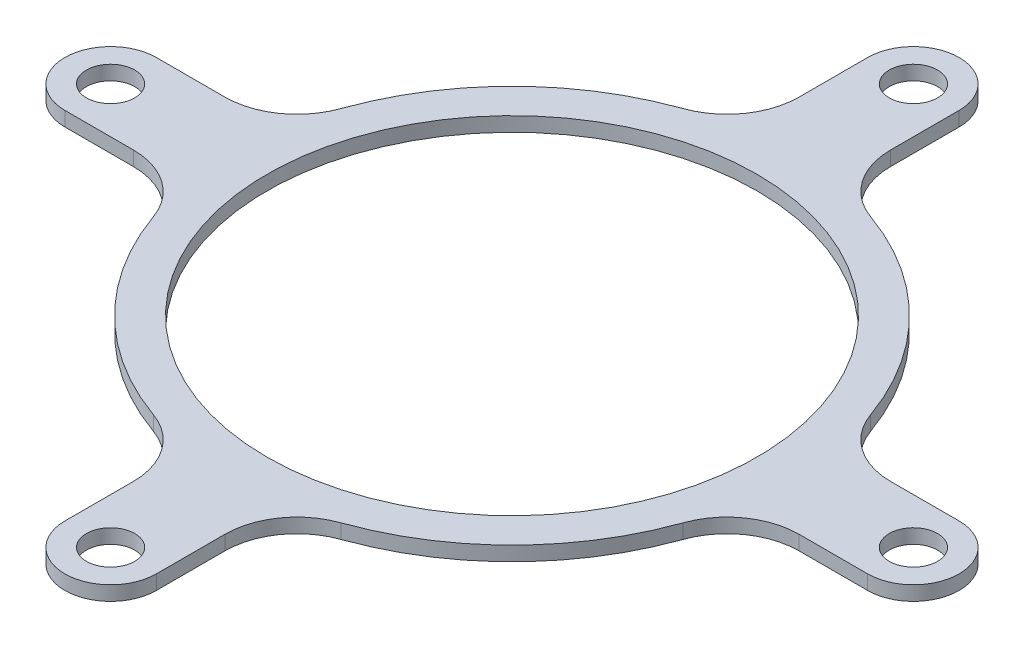
SolidWorks part; units mm, degrees
ref_plane "Front Plane" through (0, 0, 0) normal (0, 0, 1) x (1, 0, 0)
ref_plane "Top Plane" through (0, 0, 0) normal (0, 1, 0) x (1, 0, 0)
ref_plane "Right Plane" through (0, 0, 0) normal (1, 0, 0) x (0, 0, -1)
sketch "Sketch1" plane through (0, 0, 0) normal (0, 1, 0) x (1, 0, 0)
  circle A0 centre (0, 0) radius 34
  circle A1 centre (0, 0) radius 39
  dimension "innerDiam" = 68
  dimension "outerDiam" = 78
extrude "Boss-Extrude1" add sketch "Sketch1" along normal mid plane 2
sketch "Sketch2" plane through (0, 1, 0) normal (0, 1, 0) x (1, 0, 0)
  line L0 (0, 0) -> (0, 38.8704) construction
  line L1 (-6.35, 46.1917) -> (-6.35, 55.7)
  line L2 (6.35, 55.7) -> (6.35, 46.1917)
  arc A0 (-6.35, 55.7) -> (6.35, 55.7) centre (0, 55.7) cw
  arc A1 (6.35, 46.1917) -> (13.0133, 36.7649) centre (16.35, 46.1917) ccw
  circle A2 centre (0, 0) radius 39 construction
  arc A3 (-6.35, 46.1917) -> (-13.0133, 36.7649) centre (-16.35, 46.1917) cw
  arc A4 (13.0133, 36.7649) -> (-13.0133, 36.7649) centre (0, 0) ccw
  circle A5 centre (0, 0) radius 55.7 construction
  circle A6 centre (0, 55.7) radius 3.35
  dimension "supportsDiam" = 111.4
  dimension "rodDiam" = 6.7
  dimension "D3" = 3
  dimension "D4" = 10
extrude "Boss-Extrude2" add sketch "Sketch2" against normal up to surface (2 mm away) up to face at (0, -1, 39)
pattern_circular "CirPattern1" count 4 over 360 about axis through (0, 0, 0) along (0, 1, 0) of "Boss-Extrude2"
